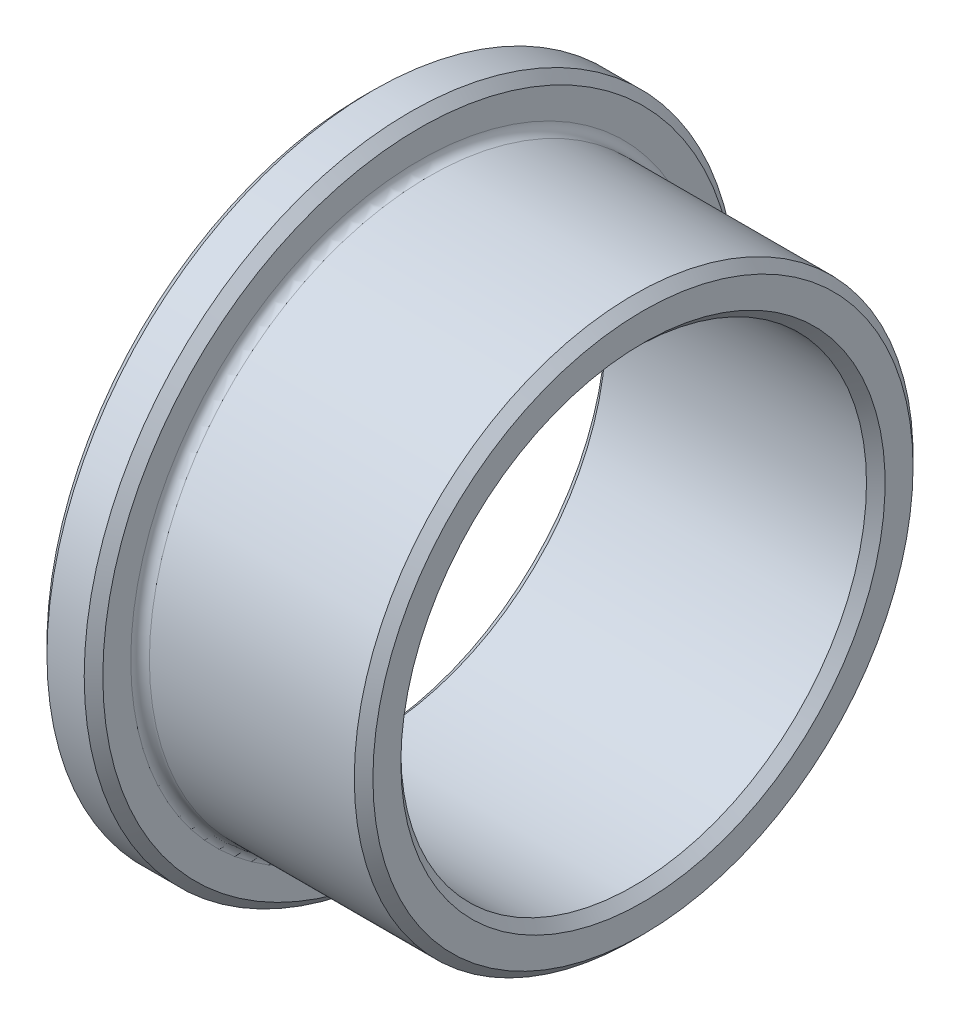
SolidWorks part; units mm, degrees
material "Phosphor bronze 10% D, UNS C52400"
ref_plane "Front Plane" through (0, 0, 0) normal (0, 0, 1) x (1, 0, 0)
ref_plane "Top Plane" through (0, 0, 0) normal (0, 1, 0) x (1, 0, 0)
ref_plane "Right Plane" through (0, 0, 0) normal (1, 0, 0) x (0, 0, -1)
sketch "Sketch1" plane through (0, 0, 0) normal (0, 0, 1) x (1, 0, 0)
  line L0 (0, 25) -> (30, 25)
  line L1 (30, 25) -> (30, 30)
  line L2 (30, 30) -> (6, 30)
  line L3 (6, 30) -> (6, 35)
  line L4 (6, 35) -> (0, 35)
  line L5 (0, 35) -> (0, 25)
  line L6 (0, 0) -> (44.8454, 0) construction
  dimension "D1" = 50
  dimension "D2" = 6
  dimension "D3" = 70
  dimension "D4" = 30
  dimension "D5" = 60
revolve "Revolve1" add sketch "Sketch1" angle 360 about L6
chamfer "Chamfer1" distance 1 angle 45 5 edges at (0, 0, 25) (30, 0, 25) (6, 0, 35) (0, 0, 35) (30, 0, 30)
fillet "Fillet1" radius 1 1 edges at (6, 0, 30)
